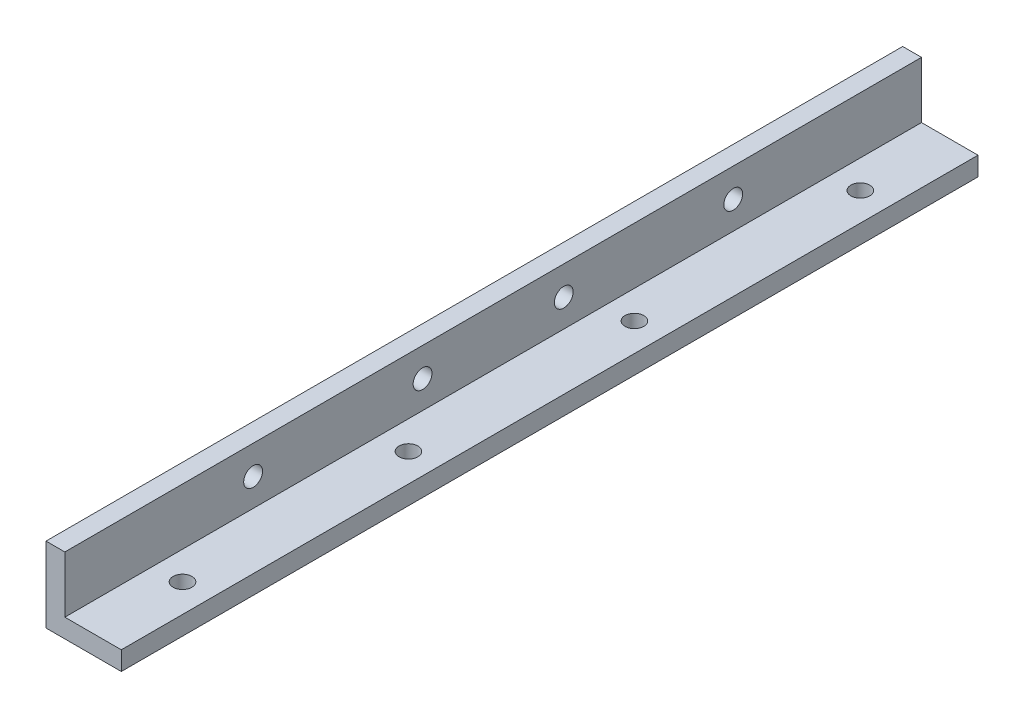
SolidWorks part; units mm, degrees
material "Aluminum"
ref_plane "Front Plane" through (0, 0, 0) normal (0, 0, 1) x (1, 0, 0)
ref_plane "Top Plane" through (0, 0, 0) normal (0, 1, 0) x (1, 0, 0)
ref_plane "Right Plane" through (0, 0, 0) normal (1, 0, 0) x (0, 0, -1)
sketch "Sketch1" plane through (0, 0, 0) normal (0, 0, 1) x (1, 0, 0)
  line L1 (0, 0) -> (5, 0)
  line L2 (0, 0) -> (0, 20)
  line L3 (0, 20) -> (5, 20)
  line L4 (5, 5) -> (5, 20)
  line L5 (0, 0) -> (20, 0)
  line L6 (0, 0) -> (0, 5)
  line L7 (5, 5) -> (20, 5)
  line L8 (20, 0) -> (20, 5)
  dimension "D1" = 20
  dimension "D2" = 20
  dimension "D3" = 5
  dimension "D4" = 5
extrude "Boss-Extrude1" add sketch "Sketch1" along normal blind 227.5 contours L5 L8 L7 L4 L3 L2 L1
hole_wizard "Tap Drill for M5x0.8 Tap1" positions "Sketch5" profile "Sketch4" hole size "M5x0.8" standard "ANSI Metric" end condition through all
sketch "Sketch5" plane through (0, 5, 0) normal (0, 1, 0) x (1, 0, 0)
  line L0 (20, -113.75) -> (58.4469, -113.75) construction
  line L1 (20, -227.5) -> (20, 0) construction
  point P0 (12.5, -203.75)
  point P2 (12.5, -143.75)
  point P4 (12.5, -83.75)
  point P6 (12.5, -23.75)
  dimension "D1" = 30
  dimension "D2" = 60
  dimension "D3" = 60
  dimension "D4" = 30
sketch "Sketch4" plane through (12.5, 5, 203.75) normal (1, 0, 0) x (0, 0, 1)
  line L0 (0, 0) -> (0, 5)
  line L1 (0, 5) -> (2.5, 5)
  line L2 (2.5, 5) -> (2.5, 0)
  line L5 (2.5, 0) -> (0, 0)
  line L11 (0, -6.35) -> (0, 107.95) construction
  dimension "Thru Hole Dia." = 5
  dimension "Thru Hole Depth" = 5
hole_wizard "Ø5.0 (5) Diameter Hole1" positions "Sketch8" profile "Sketch6" hole size "Ø5.0" standard "ANSI Metric" end condition through all
sketch "Sketch8" plane through (5, 0, 0) normal (1, 0, 0) x (0, 0, -1)
  line L0 (-227.5, 5) -> (-227.5, 20) construction
  line L1 (0, 5) -> (0, 20) construction
  point P0 (-177.5, 12.3462)
  point P2 (-132.5, 12.3462)
  point P6 (-95, 12.3462)
  point P8 (-50, 12.3462)
  dimension "D1" = 50
  dimension "D2" = 45
  dimension "D3" = 45
  dimension "D4" = 50
sketch "Sketch6" plane through (5, 12.3462, 177.5) normal (0, 1, 0) x (0, 0, -1)
  line L0 (0, 0) -> (0, 5)
  line L1 (0, 5) -> (2.5, 5)
  line L2 (2.5, 5) -> (2.5, 0)
  line L5 (2.5, 0) -> (0, 0)
  line L11 (0, -6.35) -> (0, 107.95) construction
  dimension "Thru Hole Dia." = 5
  dimension "Thru Hole Depth" = 5
